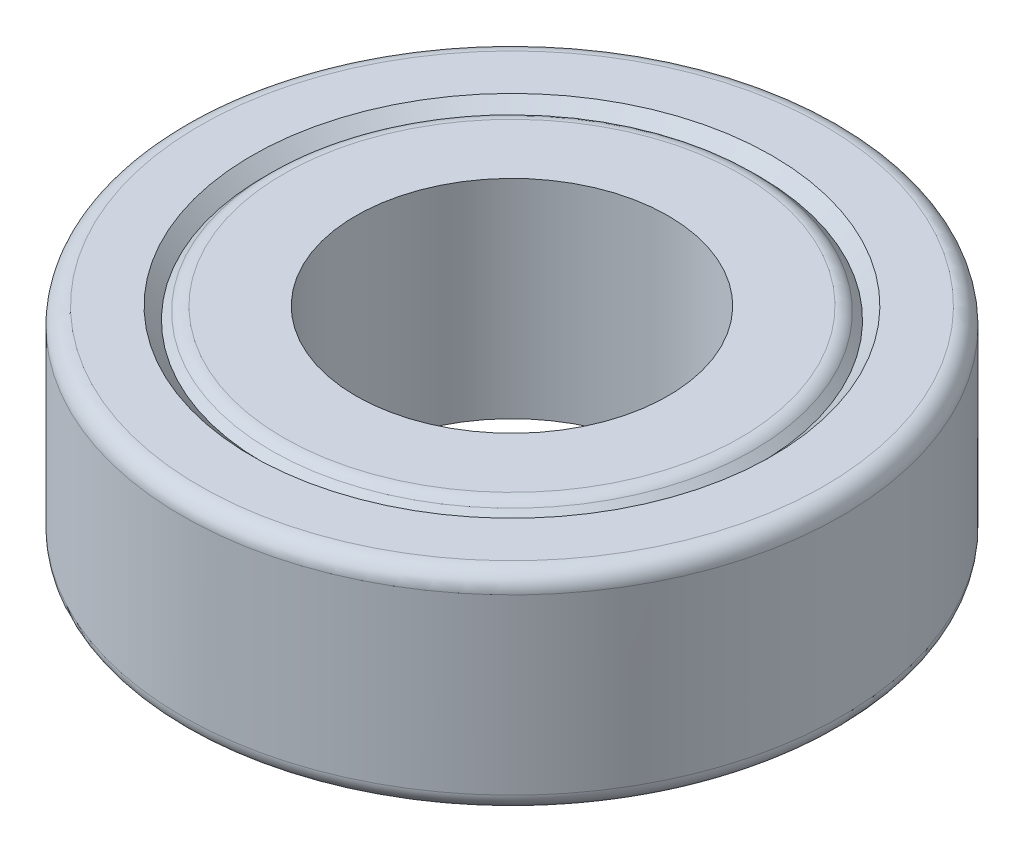
SolidWorks part; units mm, degrees
ref_plane "Plan de face" through (0, 0, 0) normal (0, 0, 1) x (1, 0, 0)
ref_plane "Plan de dessus" through (0, 0, 0) normal (0, 1, 0) x (1, 0, 0)
ref_plane "Plan de droite" through (0, 0, 0) normal (1, 0, 0) x (0, 0, -1)
sketch "Esquisse1" plane through (0, 0, 0) normal (0, 0, 1) x (1, 0, 0)
  line L0 (0, 0) -> (0, 6.4323) construction
  line L1 (-9.5, -3) -> (-9.5, 3)
  line L2 (-9.5, 3) -> (-7.5, 3)
  line L3 (-7.5, 3) -> (-7.1464, 2.6464)
  line L4 (-7.1464, 2.6464) -> (-6.7929, 3)
  line L5 (-6.7929, 3) -> (-4.5, 3)
  line L6 (-4.5, 3) -> (-4.5, -3)
  line L7 (-9.5, 0) -> (-4.5, 0) construction
  line L8 (-6.7929, -3) -> (-4.5, -3)
  line L9 (-7.1464, -2.6464) -> (-6.7929, -3)
  line L10 (-7.5, -3) -> (-7.1464, -2.6464)
  line L11 (-9.5, -3) -> (-7.5, -3)
  dimension "D1" = 6
  dimension "D2" = 4.5
  dimension "D3" = 2
  dimension "D4" = 0.5
  dimension "D5" = 5
revolve "Révolution1" add sketch "Esquisse1" angle 360 about L0
fillet "Congé2" radius 0.5 2 edges at (0, 3, -6.7929) (0, -3, -6.7929)
fillet "Congé3" radius 0.5 2 edges at (0, -3, -9.5) (0, 3, -9.5)
